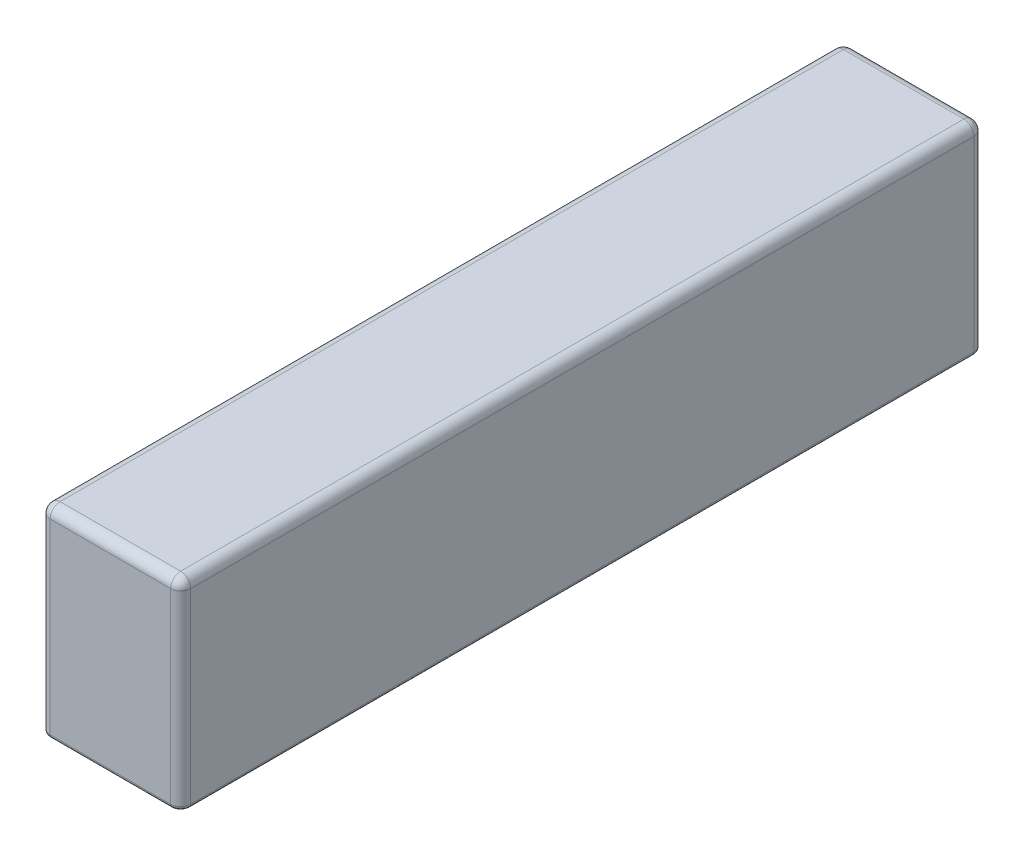
SolidWorks part; units mm, degrees
ref_plane "Front Plane" through (0, 0, 0) normal (0, 0, 1) x (1, 0, 0)
ref_plane "Top Plane" through (0, 0, 0) normal (0, 1, 0) x (1, 0, 0)
ref_plane "Right Plane" through (0, 0, 0) normal (1, 0, 0) x (0, 0, -1)
sketch "Sketch1" plane through (0, 0, 0) normal (0, 1, 0) x (1, 0, 0)
  line L1 (-3.5, -20) -> (3.5, -20)
  line L2 (-3.5, -20) -> (-3.5, 20)
  line L3 (-3.5, 20) -> (3.5, 20)
  line L4 (3.5, -20) -> (3.5, 20)
  line L5 (-3.5, -20) -> (3.5, 20) construction
  line L6 (-3.5, 20) -> (3.5, -20) construction
  point P0 (0, 0)
  dimension "D1" = 7
  dimension "D2" = 40
extrude "Boss-Extrude1" add sketch "Sketch1" along normal mid plane 10
fillet "Fillet1" radius 0.5 8 edges at (3.5, 0, -20) (3.5, 0, 20) (-3.5, 0, 20) (-3.5, 0, -20) (0, 5, -20) (3.5, 5, 0) (0, 5, 20) (-3.5, 5, 0)
fillet "Fillet2" radius 0.2 8 edges at (-3.3536, -5, -19.8536) (-3.5, -5, 0) (-3.3536, -5, 19.8536) (0, -5, 20) (3.3536, -5, 19.8536) (3.5, -5, 0) (3.3536, -5, -19.8536) (0, -5, -20)
